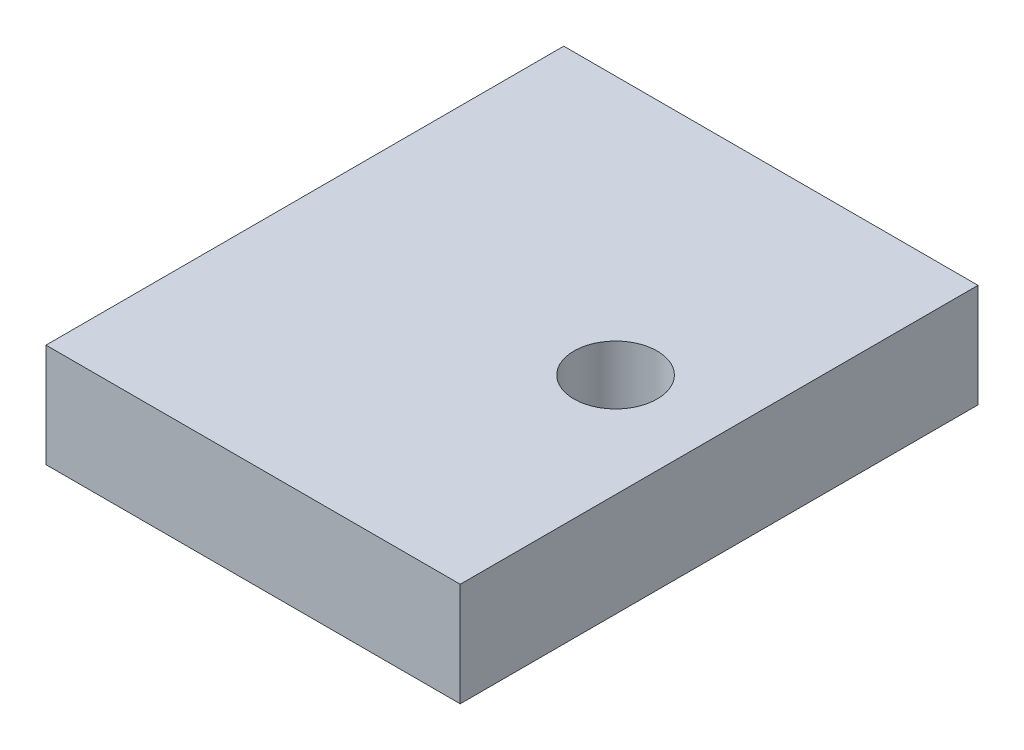
SolidWorks part; units mm, degrees
ref_plane "Front Plane" through (0, 0, 0) normal (0, 0, 1) x (1, 0, 0)
ref_plane "Top Plane" through (0, 0, 0) normal (0, 1, 0) x (1, 0, 0)
ref_plane "Right Plane" through (0, 0, 0) normal (1, 0, 0) x (0, 0, -1)
sketch "Sketch2" plane through (0, 0, 0) normal (0, 1, 0) x (1, 0, 0)
  line L1 (0, 0) -> (25.4, 0)
  line L2 (0, 0) -> (0, 31.75)
  line L3 (0, 31.75) -> (25.4, 31.75)
  line L12 (25.4, 31.75) -> (25.4, 0)
  dimension "D1" = 25.4
  dimension "D2" = 31.75
extrude "Boss-Extrude1" add sketch "Sketch2" along normal blind 6.35
hole_wizard "1/4-20 Tapped Hole1" positions "3DSketch1" profile "Sketch3" tap size "1/4-20" standard "ANSI Inch"
sketch3d "3DSketch1"
  line L0 (0, 6.35, -31.75) -> (25.4, 6.35, -31.75) construction
  line L1 (25.4, 6.35, -31.75) -> (25.4, 6.35, 0) construction
  point P0 (19.05, 6.35, -15.875)
  dimension "D1" = 15.875
  dimension "D2" = 6.35
sketch "Sketch3" plane through (19.05, 6.35, -15.875) normal (1, 0, 0) x (0, 0, 1)
  line L0 (0, 0) -> (0, 20.5838)
  line L1 (0, 20.5838) -> (2.5527, 19.05)
  line L2 (2.5527, 19.05) -> (2.5527, 0)
  line L5 (2.5527, 0) -> (0, 0)
  line L10 (0, 20.5838) -> (-2.5527, 19.05) construction
  line L11 (0, -6.35) -> (0, 107.95) construction
  dimension "Tap Drill Dia." = 5.1054
  dimension "Tap Drill Depth" = 19.05
  dimension "Drill Angle" = 118
cosmetic thread "Hole Thread1" parameters "D1"=6.35, "D2"=6.35
